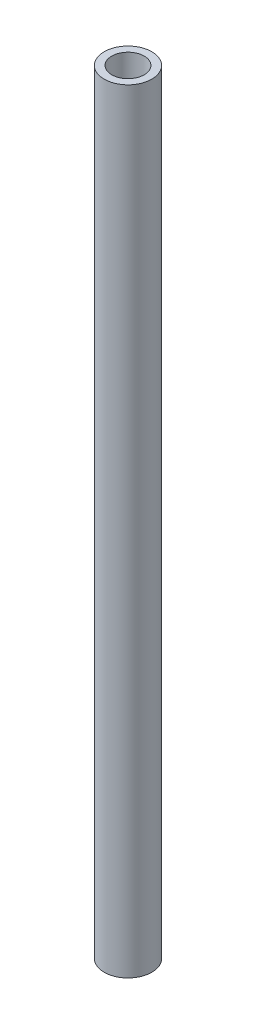
SolidWorks part; units mm, degrees
ref_plane "Front Plane" through (0, 0, 0) normal (0, 0, 1) x (1, 0, 0)
ref_plane "Top Plane" through (0, 0, 0) normal (0, 1, 0) x (1, 0, 0)
ref_plane "Right Plane" through (0, 0, 0) normal (1, 0, 0) x (0, 0, -1)
sketch "Sketch1" plane through (0, 0, 0) normal (0, 1, 0) x (1, 0, 0)
  circle A0 centre (0, 0) radius 4
  dimension "D1" = 8
extrude "Boss-Extrude1" add sketch "Sketch1" along normal blind 130
shell "Shell1" thickness 1.27
